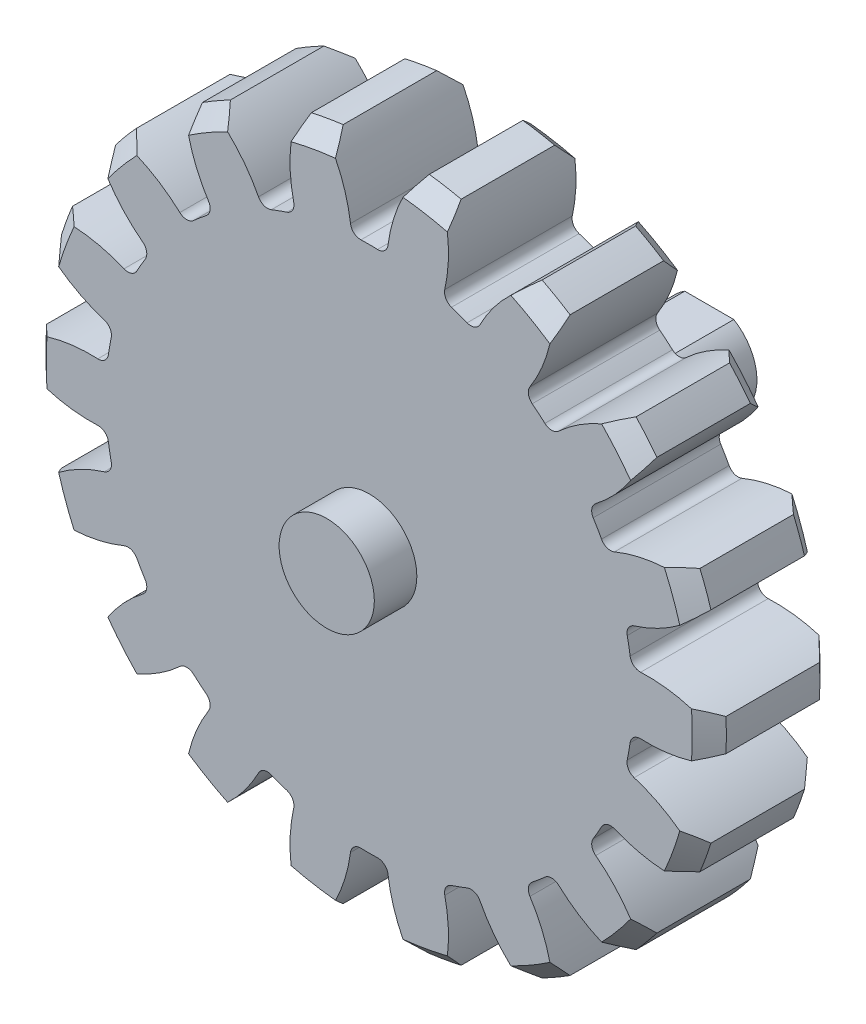
SolidWorks part; units mm, degrees
ref_plane "Přední rovina" through (0, 0, 0) normal (0, 0, 1) x (1, 0, 0)
ref_plane "Horní rovina" through (0, 0, 0) normal (0, 1, 0) x (1, 0, 0)
ref_plane "Pravá rovina" through (0, 0, 0) normal (1, 0, 0) x (0, 0, -1)
sketch "Skica1" plane through (0, 0, 0) normal (0, 0, 1) x (1, 0, 0)
  circle A0 centre (0, 0) radius 20
  circle A1 centre (0, 0) radius 18 construction
  dimension "D1" = 40
  dimension "D2" = 36
extrude "Přidat vysunutím1" add sketch "Skica1" along normal blind 7.5
sketch "Skica2" plane through (0, 0, 0) normal (0, 0, 1) x (1, 0, 0)
  line L0 (0, 20) -> (0, 0) construction
  line L1 (0, 0) -> (6.8404, 18.7939) construction
  line L2 (0, 0) -> (3.473, 19.6962) construction
  line L3 (0, 0) -> (-1.0473, 15.4646) construction
  line L4 (-1.5688, 17.9315) -> (1.5688, 17.9315) construction
  line L5 (1.5688, 17.9315) -> (4.6587, 17.3867) construction
  line L6 (-2.2744, 19.8703) -> (0, 13.6213) construction
  arc A0 (1.0473, 15.4646) -> (-1.0473, 15.4646) centre (0, 0) ccw
  circle A1 centre (0, 0) radius 16 construction
  circle A2 centre (0, 0) radius 20 construction
  arc A3 (-2.5335, 19.8389) -> (-1.0473, 15.4646) centre (-10.0152, 14.8573) cw
  arc A4 (2.5335, 19.8389) -> (1.0473, 15.4646) centre (10.0152, 14.8573) ccw
  circle A5 centre (0, 0) radius 18 construction
  arc A6 (-2.5335, 19.8389) -> (2.5335, 19.8389) centre (0, 0) cw
  dimension "D2" = 4.5
  dimension "D3" = 0.5
  dimension "D4" = 20
  dimension "D5" = 20
  dimension "D6" = 0.5
extrude "Odebrat vysunutím1" cut sketch "Skica2" along normal blind 7.5
fillet "Zaoblit2" radius 0.6 2 edges at (1.0473, 15.4646, 3.75) (-1.0473, 15.4646, 3.75)
chamfer "Zkosení1" distance 1 2 edges at (0, -20, 0) (0, -20, 7.5)
pattern_circular "Kruhové pole1" count 18 every 20 about axis through (0, 0, 0) along (0, 0, 1) of "Odebrat vysunutím1", "Zaoblit2"
sketch "Skica3" plane through (0, 0, 0) normal (0, 0, 1) x (1, 0, 0)
  circle A0 centre (0, 0) radius 2.8
  dimension "D1" = 5.6
extrude "Přidat vysunutím2" add sketch "Skica3" against normal blind 12.5 and the other way blind 10
sketch "Skica4" plane through (0, 0, -12.5) normal (0, 0, -1) x (-1, 0, 0)
  line L0 (-1.4422, 2.4) -> (1.4422, 2.4)
  circle A0 centre (0, 0) radius 2.8
  circle A1 centre (0, 0) radius 2.8 construction
  circle M3 centre (0, 0) radius 2.8
  dimension "D1" = 2.4
extrude "Odebrat vysunutím2" cut sketch "Skica4" against normal blind 10 contours L0 M3
equation "\"Module\"= 2mm"
equation "\"Number of teeth\"= 18"
equation "\"Pressure angle\"= 20"
equation "\"D1@Skica1\"=(\"Number of teeth\" + 2) * \"Module\""
equation "\"D2@Skica1\"= \"Number of teeth\" * \"Module\""
equation "\"D1@Skica2\"= \"Module\" * 2"
equation "\"D2@Skica2\"=\"Module\" * if( \"Module\" => 1.25, 2.25, 2.4 )"
equation "\"D4@Skica2\"= 360 / \"Number of teeth\""
equation "\"D5@Skica2\"=\"Pressure angle\""
equation "\"DC1@Zaoblit\"= 0.3 * \"Module\""
equation "\"D1@Kruhové pole1\"=\"Number of teeth\""
equation "\"D2@Kruhové pole1\"= 360 / \"Number of teeth\""
